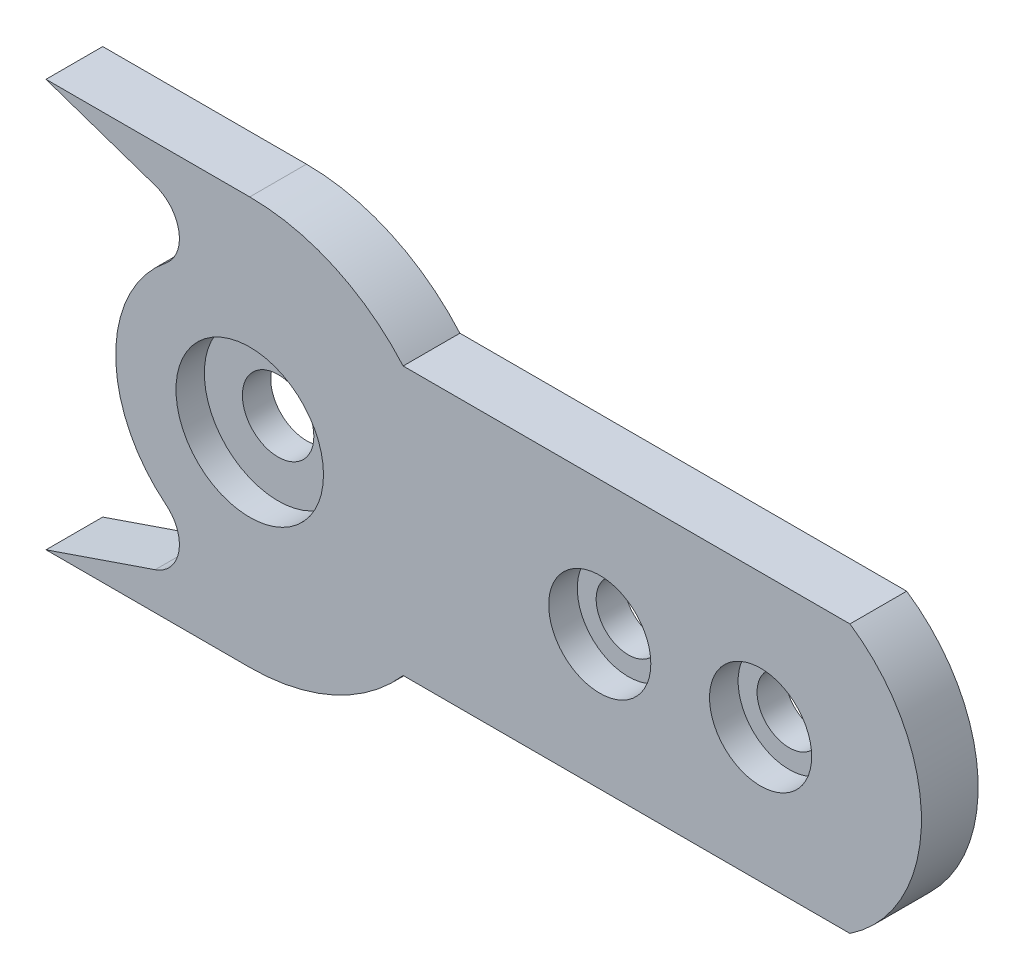
SolidWorks part; units mm, degrees
material "6061-T6 (SS)"
ref_plane "Front Plane" through (0, 0, 0) normal (0, 0, 1) x (1, 0, 0)
ref_plane "Top Plane" through (0, 0, 0) normal (0, 1, 0) x (1, 0, 0)
ref_plane "Right Plane" through (0, 0, 0) normal (1, 0, 0) x (0, 0, -1)
sketch "Sketch1" plane through (0, 0, 0) normal (0, 0, 1) x (1, 0, 0)
  line L0 (0, -45) -> (0, -57) construction
  line L1 (-57, -57) -> (0, -37.5)
  line L2 (-57, -57) -> (0, -57)
  line L3 (-45, 0) -> (-57, 0) construction
  line L4 (-57, 57) -> (0, 57)
  line L5 (-57, 57) -> (0, 37.5)
  line L6 (0, 0) -> (57, 0) construction
  line L7 (42.9273, -37.5) -> (167.9273, -37.5)
  line L8 (42.9273, 37.5) -> (167.9273, 37.5)
  line L9 (167.9273, 37.5) -> (167.9273, -37.5) construction
  circle A0 centre (0, 0) radius 45 construction
  circle A1 centre (0, 0) radius 57 construction
  arc A2 (0, 37.5) -> (0, -37.5) centre (0, 0) ccw
  arc A3 (0, -57) -> (42.9273, -37.5) centre (0, 0) ccw
  arc A4 (0, 57) -> (42.9273, 37.5) centre (0, 0) cw
  circle A5 centre (0, 0) radius 10
  arc A6 (167.9273, 37.5) -> (167.9273, -37.5) centre (142.771, 0) cw
  point P21 (187.9273, 0)
  dimension "D1" = 90
  dimension "D4" = 75
  dimension "D8" = 20
  dimension "D2" = 12
  dimension "D3" = 12
  dimension "D5" = 75
  dimension "D6" = 18.886
  dimension "D7" = 125
  dimension "D9" = 20
extrude "Boss-Extrude1" add sketch "Sketch1" along normal mid plane 15.875
fillet "Fillet1" radius 10 2 edges at (0, -37.5, 0) (0, 37.5, 0)
sketch "Sketch2" plane through (0, 0, 7.9375) normal (0, 0, 1) x (1, 0, 0)
  circle A0 centre (142.9273, 0) radius 14.2875
  circle A1 centre (97.9273, 0) radius 14.2875
  dimension "D2" = 28.575
  dimension "D1" = 25
  dimension "D3" = 45
extrude "Cut-Extrude1" cut sketch "Sketch2" against normal blind 8
sketch "Sketch3" plane through (0, 0, 7.9375) normal (0, 0, 1) x (1, 0, 0)
  circle A1 centre (142.9273, 0) radius 14.2875 construction
  circle A2 centre (97.9273, 0) radius 9
  circle A3 centre (142.9273, 0) radius 9
  dimension "D1" = 18
extrude "Cut-Extrude2" cut sketch "Sketch3" against normal through all
sketch "Sketch4" plane through (0, 0, 7.9375) normal (0, 0, 1) x (1, 0, 0)
  circle A0 centre (0, 0) radius 20.6375
  dimension "D1" = 41.275
extrude "Cut-Extrude3" cut sketch "Sketch4" against normal blind 7.9375
equation "\"D1@Boss-Extrude1\"=0.625in"
equation "\"D2@Sketch2\"=1.125in"
equation "\"D1@Sketch4\"=1.625in"
